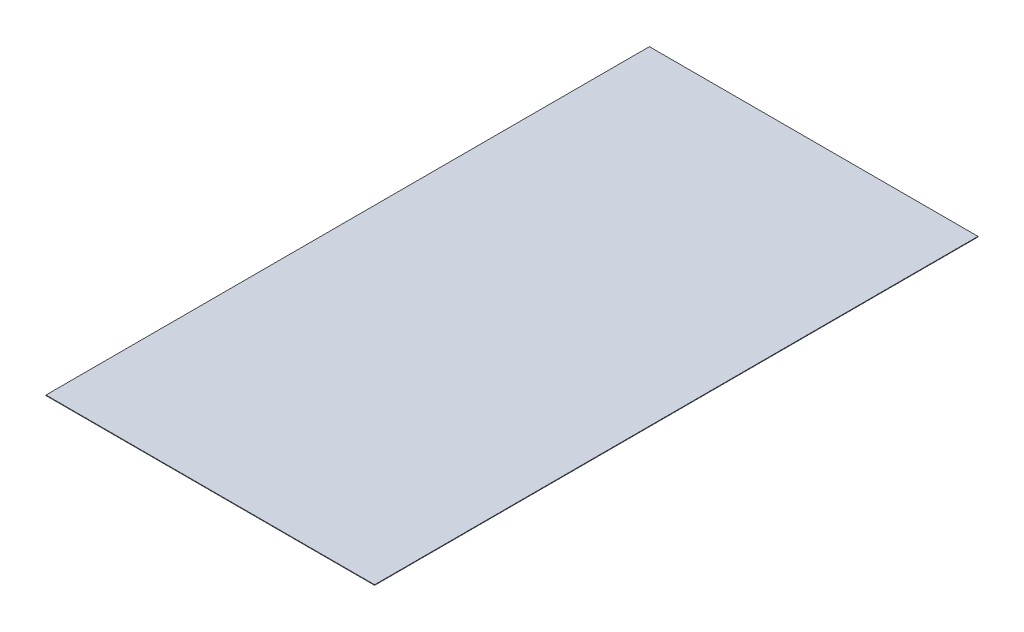
SolidWorks part; units mm, degrees
ref_plane "Front Plane" through (0, 0, 0) normal (0, 0, 1) x (1, 0, 0)
ref_plane "Top Plane" through (0, 0, 0) normal (0, 1, 0) x (1, 0, 0)
ref_plane "Right Plane" through (0, 0, 0) normal (1, 0, 0) x (0, 0, -1)
sketch "Sketch1" plane through (0, 0, 0) normal (0, 1, 0) x (1, 0, 0)
  line L1 (74.7852, -1042.1419) -> (-523.2148, -1042.1419)
  line L2 (74.7852, -1042.1419) -> (74.7852, 55.8581)
  line L3 (74.7852, 55.8581) -> (-523.2148, 55.8581)
  line L4 (-523.2148, -1042.1419) -> (-523.2148, 55.8581)
  dimension "D1" = 1098
  dimension "D2" = 598
extrude "Boss-Extrude1" add sketch "Sketch1" along normal blind 1
